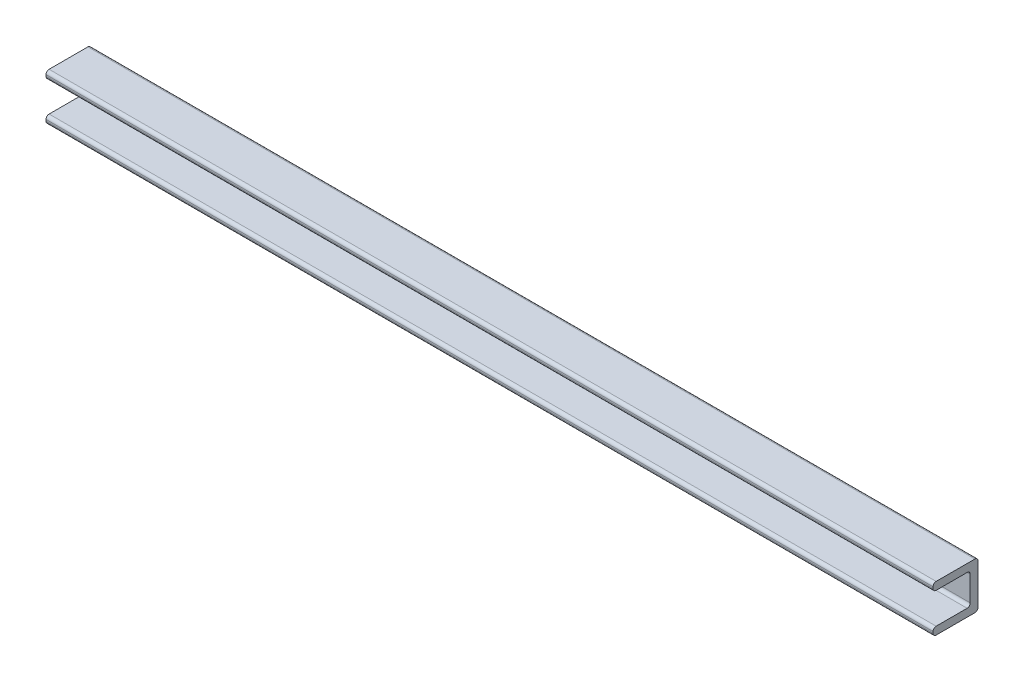
SolidWorks part; units mm, degrees
material "1023 Carbon Steel Sheet (SS)"
ref_plane "Ön Düzlem" through (0, 0, 0) normal (0, 0, 1) x (1, 0, 0)
ref_plane "Üst Düzlem" through (0, 0, 0) normal (0, 1, 0) x (1, 0, 0)
ref_plane "Sağ Düzlem" through (0, 0, 0) normal (1, 0, 0) x (0, 0, -1)
sketch "Sketch1" plane through (0, 0, 0) normal (1, 0, 0) x (0, 0, -1)
  line L0 (-168, 10) -> (-188, 10)
  line L1 (-190, 8) -> (-190, -8)
  line L2 (-188, -10) -> (-168, -10)
  line L3 (-168, 15) -> (-193, 15)
  line L4 (-195, 13) -> (-195, -13)
  line L5 (-193, -15) -> (-168, -15)
  line L6 (-166, 13) -> (-166, 12)
  line L7 (-166, -12) -> (-166, -13)
  line L8 (-177.3019, 10) -> (-190, 10) construction
  line L9 (-195, 15) -> (-195, -15) construction
  line L10 (-195, -15) -> (-166, -15) construction
  line L11 (-190, 10) -> (-190, -10) construction
  line L12 (-190, -10) -> (-166, -10) construction
  line L13 (-177.3019, 15) -> (-195, 15) construction
  line L14 (0, -1000) -> (0, 49000) construction
  line L15 (166, -12) -> (166, -13)
  line L16 (166, 13) -> (166, 12)
  line L17 (193, -15) -> (168, -15)
  line L18 (195, 13) -> (195, -13)
  line L19 (168, 15) -> (193, 15)
  line L20 (188, -10) -> (168, -10)
  line L21 (190, 8) -> (190, -8)
  line L22 (168, 10) -> (188, 10)
  arc A0 (-168, 10) -> (-166, 12) centre (-168, 12) ccw
  arc A1 (-195, -13) -> (-193, -15) centre (-193, -13) ccw
  arc A2 (-188, 10) -> (-190, 8) centre (-188, 8) ccw
  arc A3 (-190, -8) -> (-188, -10) centre (-188, -8) ccw
  arc A4 (-168, -10) -> (-166, -12) centre (-168, -12) cw
  arc A5 (-168, -15) -> (-166, -13) centre (-168, -13) ccw
  arc A6 (-168, 15) -> (-166, 13) centre (-168, 13) cw
  arc A7 (-193, 15) -> (-195, 13) centre (-193, 13) ccw
  arc A8 (193, 15) -> (195, 13) centre (193, 13) cw
  arc A9 (168, 15) -> (166, 13) centre (168, 13) ccw
  arc A10 (168, -15) -> (166, -13) centre (168, -13) cw
  arc A11 (168, -10) -> (166, -12) centre (168, -12) ccw
  arc A12 (190, -8) -> (188, -10) centre (188, -8) cw
  arc A13 (188, 10) -> (190, 8) centre (188, 8) cw
  arc A14 (195, -13) -> (193, -15) centre (193, -13) cw
  arc A15 (168, 10) -> (166, 12) centre (168, 12) cw
  point P6 (-190, 0)
  point P16 (-166, 10)
  point P61 (166, 10)
  point P62 (190, 0)
  dimension "D5" = 2
  dimension "D1" = 20
  dimension "D2" = 24
  dimension "D3" = 190
  dimension "D4" = 5
sketch "Sketch4" plane through (0, 0, 0) normal (1, 0, 0) x (0, 0, -1)
  line L0 (195, 13) -> (195, -13) construction
  line L1 (190, 8) -> (190, -8) construction
  line L2 (188, -10) -> (168, -10) construction
  line L3 (193, -15) -> (168, -15) construction
  line L4 (166, -12) -> (166, -13) construction
  line L5 (166, 13) -> (166, 12) construction
  line L6 (168, 15) -> (193, 15) construction
  line L7 (168, 10) -> (188, 10) construction
  line L8 (195, 13) -> (195, -13)
  line L9 (190, 8) -> (190, -8)
  line L10 (188, -10) -> (168, -10)
  line L11 (193, -15) -> (168, -15)
  line L12 (166, -12) -> (166, -13)
  line L13 (166, 13) -> (166, 12)
  line L14 (168, 15) -> (193, 15)
  line L15 (168, 10) -> (188, 10)
  arc A0 (190, 8) -> (188, 10) centre (188, 8) ccw construction
  arc A1 (195, 13) -> (193, 15) centre (193, 13) ccw construction
  arc A2 (188, -10) -> (190, -8) centre (188, -8) ccw construction
  arc A3 (193, -15) -> (195, -13) centre (193, -13) ccw construction
  arc A4 (166, -13) -> (168, -15) centre (168, -13) ccw construction
  arc A5 (168, -10) -> (166, -12) centre (168, -12) ccw construction
  arc A6 (166, 12) -> (168, 10) centre (168, 12) ccw construction
  arc A7 (168, 15) -> (166, 13) centre (168, 13) ccw construction
  arc A8 (190, 8) -> (188, 10) centre (188, 8) ccw
  arc A9 (195, 13) -> (193, 15) centre (193, 13) ccw
  arc A10 (188, -10) -> (190, -8) centre (188, -8) ccw
  arc A11 (193, -15) -> (195, -13) centre (193, -13) ccw
  arc A12 (166, -13) -> (168, -15) centre (168, -13) ccw
  arc A13 (168, -10) -> (166, -12) centre (168, -12) ccw
  arc A14 (166, 12) -> (168, 10) centre (168, 12) ccw
  arc A15 (168, 15) -> (166, 13) centre (168, 13) ccw
extrude "Boss-Extrude1" add sketch "Sketch4" along normal blind 572 from offset 30
